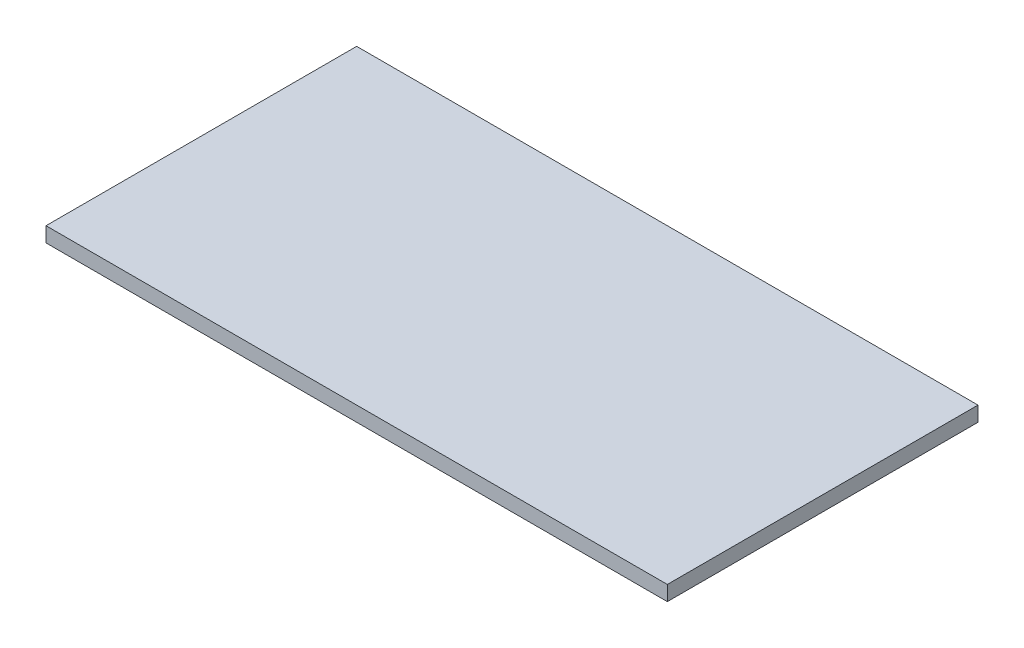
SolidWorks part; units mm, degrees
ref_plane "Front Plane" through (0, 0, 0) normal (0, 0, 1) x (1, 0, 0)
ref_plane "Top Plane" through (0, 0, 0) normal (0, 1, 0) x (1, 0, 0)
ref_plane "Right Plane" through (0, 0, 0) normal (1, 0, 0) x (0, 0, -1)
sketch "Sketch1" plane through (0, 0, 0) normal (0, 1, 0) x (1, 0, 0)
  line L1 (-50, -25) -> (50, -25)
  line L2 (-50, -25) -> (-50, 25)
  line L3 (-50, 25) -> (50, 25)
  line L4 (50, -25) -> (50, 25)
  line L5 (-50, -25) -> (50, 25) construction
  line L6 (-50, 25) -> (50, -25) construction
  point P0 (0, 0)
  dimension "D1" = 50
  dimension "D2" = 100
extrude "Boss-Extrude1" add sketch "Sketch1" along normal blind 2.4
